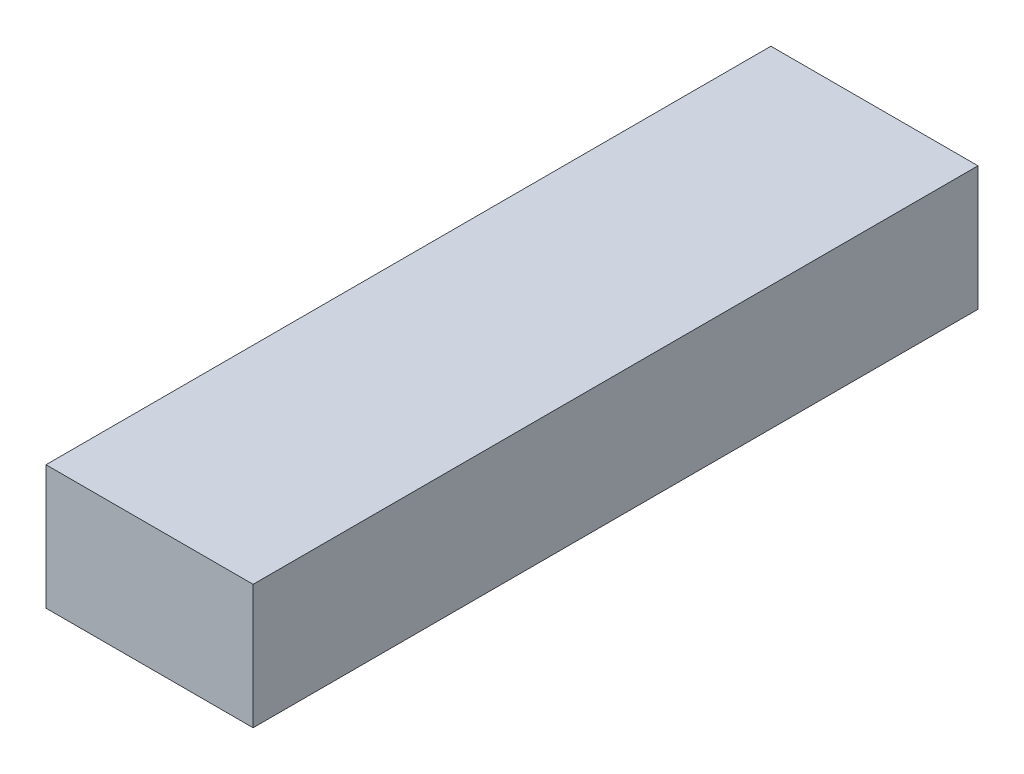
SolidWorks part; units mm, degrees
material "Kiefer"
ref_plane "Ebene vorne" through (0, 0, 0) normal (0, 0, 1) x (1, 0, 0)
ref_plane "Ebene oben" through (0, 0, 0) normal (0, 1, 0) x (1, 0, 0)
ref_plane "Ebene rechts" through (0, 0, 0) normal (1, 0, 0) x (0, 0, -1)
sketch "Skizze1" plane through (0, 0, 0) normal (0, 0, 1) x (1, 0, 0)
  line L0 (0, 0) -> (0, 40.512) construction
  line L2 (50, 30) -> (-50, 30)
  line L3 (50, 30) -> (50, -30)
  line L4 (50, -30) -> (-50, -30)
  line L5 (-50, 30) -> (-50, -30)
  line L6 (50, 30) -> (-50, -30) construction
  line L7 (50, -30) -> (-50, 30) construction
  dimension "D1" = 100
  dimension "D2" = 60
extrude "Aufsatz-Linear austragen1" add sketch "Skizze1" along normal mid plane 350
